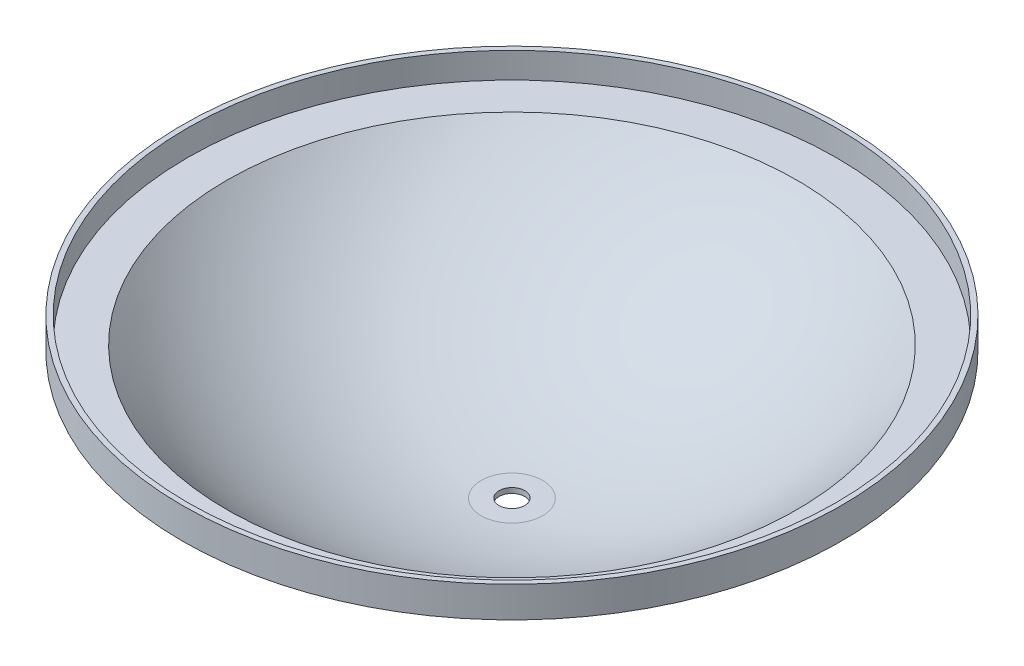
SolidWorks part; units mm, degrees
ref_plane "Front Plane" through (0, 0, 0) normal (0, 0, 1) x (1, 0, 0)
ref_plane "Top Plane" through (0, 0, 0) normal (0, 1, 0) x (1, 0, 0)
ref_plane "Right Plane" through (0, 0, 0) normal (1, 0, 0) x (0, 0, -1)
sketch "Sketch1" plane through (0, 0, 0) normal (0, 0, 1) x (1, 0, 0)
  line L0 (0, 36.2989) -> (0, -109.198) construction
  line L1 (-2.5, -72.753) -> (-6, -72.753)
  line L2 (-63, -41) -> (-63, -46)
  line L3 (-63, -46) -> (-55.3895, -46)
  line L4 (-64, -41) -> (-64, -47)
  line L5 (-64, -47) -> (-55.857, -47)
  line L6 (0, -41) -> (0, -109.198) construction
  line L7 (-2.5, -71.753) -> (-5.9587, -71.753)
  line L8 (-64, -41) -> (-63, -41)
  line L9 (-2.5, -71.753) -> (-2.5, -72.753)
  arc A0 (-55.857, -47) -> (-6, -72.753) centre (0, 0) ccw
  arc A1 (-55.3895, -46) -> (-5.9587, -71.753) centre (0, 0) ccw
  dimension "D1" = 146
  dimension "D2" = 2.5
  dimension "D3" = 64
  dimension "D4" = 6
  dimension "D5" = 1
revolve "Revolve2" add sketch "Sketch1" angle 360 about L0
